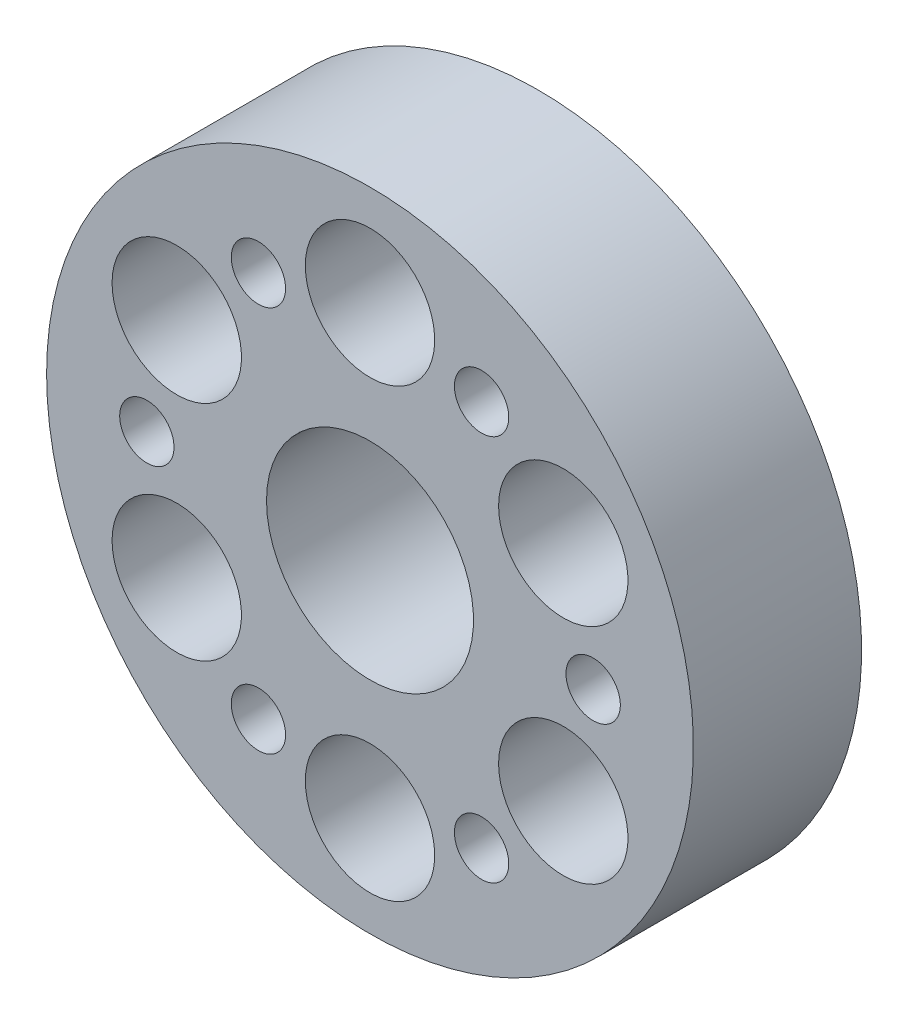
SolidWorks part; units mm, degrees
ref_plane "前视基准面" through (0, 0, 0) normal (0, 0, 1) x (1, 0, 0)
ref_plane "上视基准面" through (0, 0, 0) normal (0, 1, 0) x (1, 0, 0)
ref_plane "右视基准面" through (0, 0, 0) normal (1, 0, 0) x (0, 0, -1)
other "Configuration Table"
sketch "草图1" plane through (0, 0, 0) normal (0, 0, 1) x (1, 0, 0)
  line L0 (0, 0) -> (0, -17.25) construction
  line L1 (17.25, 0) -> (8.625, 14.9389) construction
  line L2 (8.625, 14.9389) -> (-8.625, 14.9389) construction
  line L3 (-8.625, 14.9389) -> (-17.25, 0) construction
  line L4 (-17.25, 0) -> (-8.625, -14.9389) construction
  line L5 (-8.625, -14.9389) -> (8.625, -14.9389) construction
  line L6 (8.625, -14.9389) -> (17.25, 0) construction
  line L7 (0, 0) -> (17.25, 0) construction
  line L8 (0, -17.25) -> (14.9389, -8.625) construction
  line L9 (14.9389, -8.625) -> (14.9389, 8.625) construction
  line L10 (0, 0) -> (8.625, -14.9389) construction
  line L11 (14.9389, 8.625) -> (0, 17.25) construction
  line L12 (0, 17.25) -> (-14.9389, 8.625) construction
  line L13 (-14.9389, 8.625) -> (-14.9389, -8.625) construction
  line L14 (-14.9389, -8.625) -> (0, -17.25) construction
  line L15 (0, 0) -> (-14.9389, -8.625) construction
  circle A0 centre (0, 0) radius 25
  circle A1 centre (0, 0) radius 8
  circle A2 centre (0, 0) radius 14.9389 construction
  circle A3 centre (8.625, 14.9389) radius 2.1
  circle A4 centre (17.25, 0) radius 2.1
  circle A5 centre (8.625, -14.9389) radius 2.1
  circle A6 centre (-8.625, -14.9389) radius 2.1
  circle A7 centre (-17.25, 0) radius 2.1
  circle A8 centre (-8.625, 14.9389) radius 2.1
  circle A15 centre (0, 0) radius 14.9389 construction
  circle A16 centre (0, 17.25) radius 5
  circle A17 centre (14.9389, 8.625) radius 5
  circle A18 centre (14.9389, -8.625) radius 5
  circle A19 centre (-14.9389, -8.625) radius 5
  circle A20 centre (-14.9389, 8.625) radius 5
  circle A21 centre (0, -17.25) radius 5
  dimension "D1" = 50
  dimension "D2" = 16
  dimension "D4" = 4.2
  dimension "D5" = 4.2
  dimension "D6" = 4.2
  dimension "D7" = 4.2
  dimension "D8" = 4.2
  dimension "D9" = 4.2
  dimension "D10" = 17.25
  dimension "D11" = 10
  dimension "D12" = 10
  dimension "D13" = 10
  dimension "D14" = 10
  dimension "D15" = 10
  dimension "D3" = 17.25
extrude "凸台-拉伸2" add sketch "草图1" along normal blind 13
